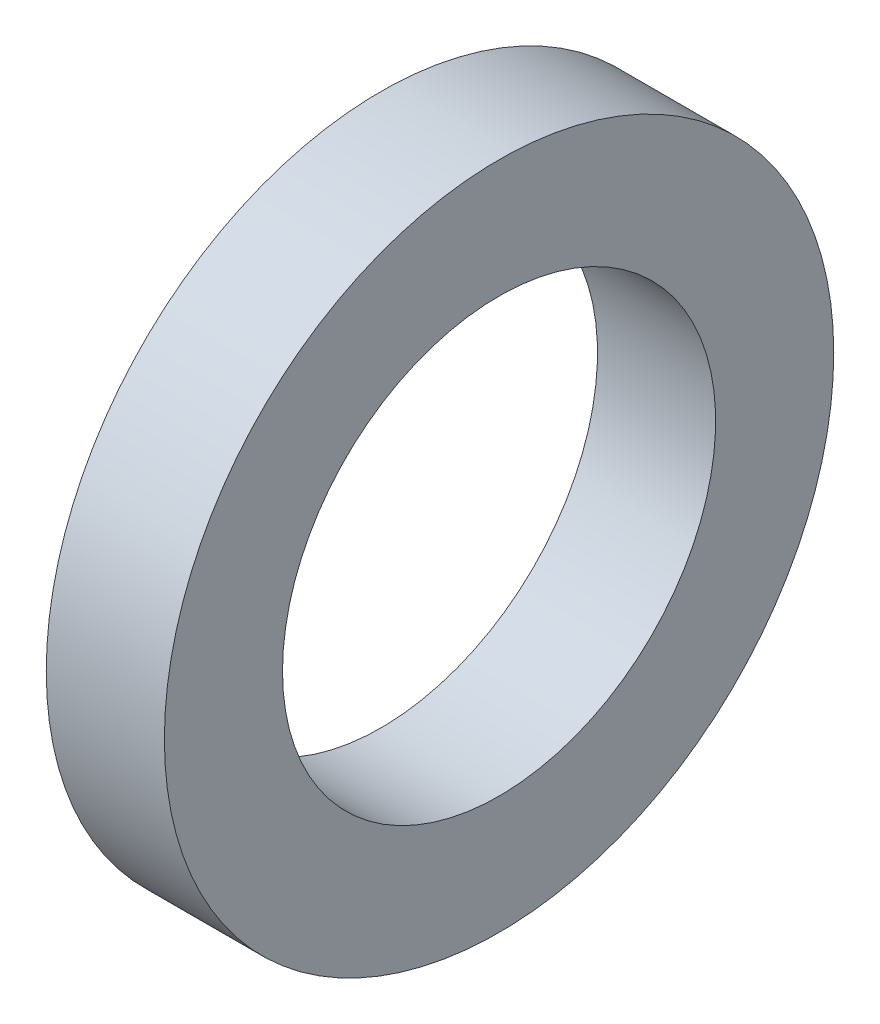
SolidWorks part; units mm, degrees
ref_plane "Front Plane" through (0, 0, 0) normal (0, 0, 1) x (1, 0, 0)
ref_plane "Top Plane" through (0, 0, 0) normal (0, 1, 0) x (1, 0, 0)
ref_plane "Right Plane" through (0, 0, 0) normal (1, 0, 0) x (0, 0, -1)
sketch "Sketch1" plane through (0, 0, 0) normal (0, 0, 1) x (1, 0, 0)
  line L0 (0, 0) -> (1.5, 0) construction
  line L1 (0, 2.75) -> (1.5, 2.75)
  line L2 (0, 2.75) -> (0, 4.25)
  line L3 (0, 4.25) -> (1.5, 4.25)
  line L4 (1.5, 2.75) -> (1.5, 4.25)
  dimension "FIX_2" = 8.5
  dimension "FIX_3" = 5.5
  dimension "FIX_1" = 1.5
revolve "Revolve1" add sketch "Sketch1" angle 360 about L0
